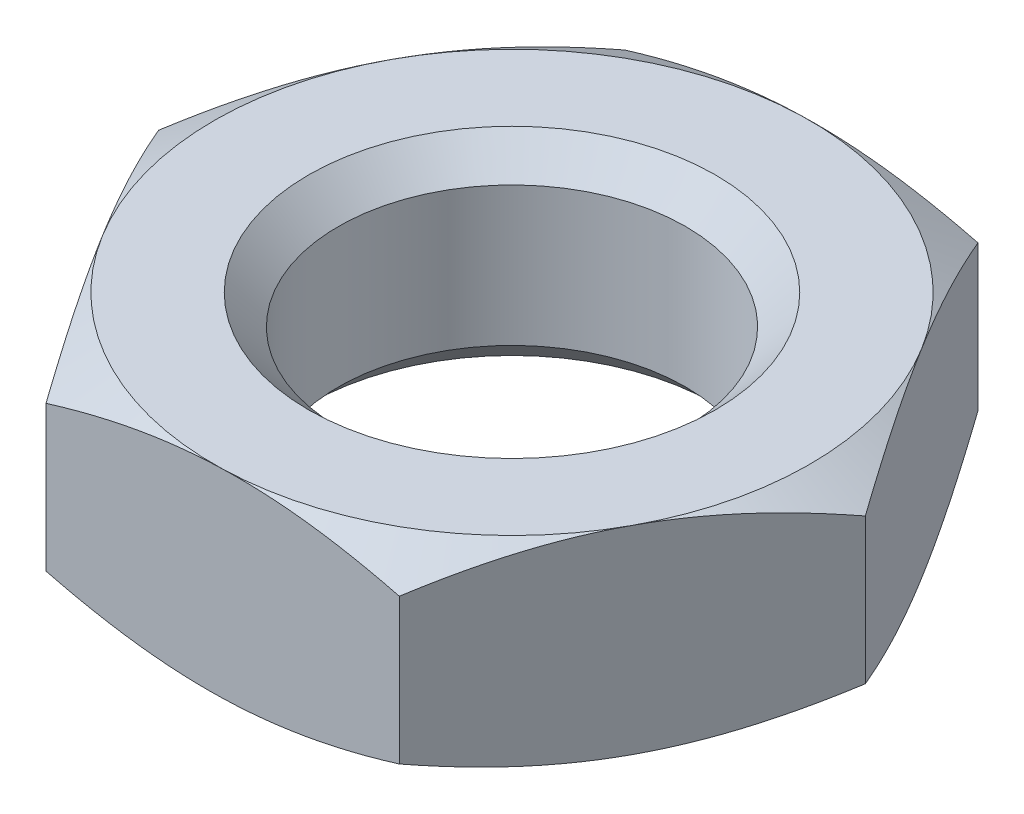
SolidWorks part; units mm, degrees
ref_plane "Front Plane" through (0, 0, 0) normal (0, 0, 1) x (1, 0, 0)
ref_plane "Top Plane" through (0, 0, 0) normal (0, 1, 0) x (1, 0, 0)
ref_plane "Right Plane" through (0, 0, 0) normal (1, 0, 0) x (0, 0, -1)
sketch "Sketch1" plane through (0, 0, 0) normal (0, 1, 0) x (1, 0, 0)
  line L1 (1.6474, 3.0473) -> (-1.8153, 2.9504)
  line L2 (-1.8153, 2.9504) -> (-3.4627, -0.0969)
  line L3 (-3.4627, -0.0969) -> (-1.6474, -3.0473)
  line L4 (-1.6474, -3.0473) -> (1.8153, -2.9504)
  line L5 (1.8153, -2.9504) -> (3.4627, 0.0969)
  line L6 (3.4627, 0.0969) -> (1.6474, 3.0473)
  circle A0 centre (0, 0) radius 3 construction
  circle A1 centre (0, 0) radius 1.75
  dimension "D1" = 3.5
  dimension "D2" = 6
extrude "Boss-Extrude1" add sketch "Sketch1" along normal blind 2
sketch "Sketch2" plane through (0, 2, 0) normal (0, 1, 0) x (1, 0, 0)
  line L0 (-1.8153, 2.9504) -> (-3.4627, -0.0969) construction
  circle A0 centre (0, 0) radius 3
extrude "Cut-Extrude1" cut sketch "Sketch2" against normal blind 177.8 draft 60 flip side to cut
sketch "Sketch3" plane through (0, 0, 0) normal (0, -1, 0) x (1, 0, 0)
  line L0 (-3.4627, 0.0969) -> (-1.6474, 3.0473) construction
  circle A0 centre (0, 0) radius 3
extrude "Cut-Extrude2" cut sketch "Sketch3" against normal blind 177.8 draft 60 flip side to cut
chamfer "Chamfer1" distance 0.3 angle 45 1 edges at (0, 2, 1.75)
chamfer "Chamfer2" distance 0.3 angle 45 1 edges at (0, 0, 1.75)
